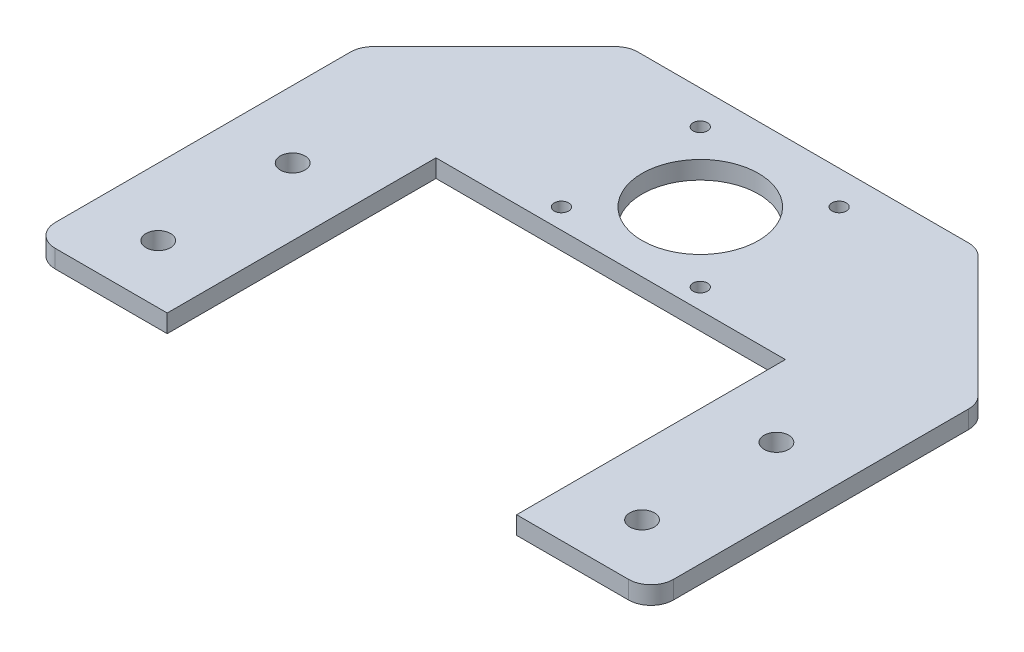
SolidWorks part; units mm, degrees
ref_plane "Front Plane" through (0, 0, 0) normal (0, 0, 1) x (1, 0, 0)
ref_plane "Top Plane" through (0, 0, 0) normal (0, 1, 0) x (1, 0, 0)
ref_plane "Right Plane" through (0, 0, 0) normal (1, 0, 0) x (0, 0, -1)
sketch "Sketch1" plane through (0, 0, 0) normal (0, 1, 0) x (1, 0, 0)
  line L0 (-69, -60) -> (-69, 43)
  line L1 (-69, 43) -> (69, 43)
  line L2 (69, 43) -> (69, -60)
  line L3 (69, -60) -> (39, -60)
  line L4 (39, -60) -> (39, 0)
  line L5 (-4.4, 0) -> (4.4, 0) construction
  line L6 (39, 0) -> (-39, 0)
  line L7 (-39, 0) -> (-39, -60)
  line L8 (-39, -60) -> (-69, -60)
  line L10 (0, 0) -> (0, 59.4938) construction
  line L11 (0, -4.4) -> (0, 4.4) construction
  circle A0 centre (0, 20) radius 13
  dimension "D7" = 26
  dimension "D1" = 78
  dimension "D2" = 60
  dimension "D3" = 60
  dimension "D4" = 43
  dimension "D5" = 30
  dimension "D6" = 30
  dimension "D8" = 20
extrude "Boss-Extrude1" add sketch "Sketch1" along normal blind 4
chamfer "Chamfer1" distance 30 angle 45 2 edges at (-69, 2, -43) (69, 2, -43)
hole_wizard "M3 Clearance Hole1" positions "Sketch3" profile "Sketch2" hole size "M3" standard "ISO"
sketch "Sketch3" plane through (0, 4, 0) normal (0, 1, 0) x (1, 0, 0)
  line L0 (0, -55) -> (0, 55) construction
  line L1 (-55, 0) -> (55, 0) construction
  line L2 (0, 47.128) -> (0, -19.6073) construction
  point P0 (-15.5, 35.5)
  point P2 (-15.5, 4.5)
  point P14 (15.5, 4.5)
  point P15 (15.5, 35.5)
  dimension "D1" = 15.5
  dimension "D2" = 15.5
  dimension "D3" = 4.5
  dimension "D4" = 31
sketch "Sketch2" plane through (-15.5, 4, -35.5) normal (1, 0, 0) x (0, 0, 1)
  line L0 (0, 0) -> (0, 8.9614)
  line L1 (0, 8.9614) -> (1.6, 8)
  line L2 (1.6, 8) -> (1.6, 0)
  line L5 (1.6, 0) -> (0, 0)
  line L10 (0, 8.9614) -> (-1.6, 8) construction
  line L11 (0, -6.35) -> (0, 107.95) construction
  dimension "Hole Dia." = 3.2
  dimension "Hole Depth" = 8
  dimension "Drill Angle" = 118
fillet "Fillet1" radius 5 6 edges at (-69, 2, 60) (-69, 2, -13) (-39, 2, -43) (39, 2, -43) (69, 2, 60) (69, 2, -13)
hole_wizard "M5 Clearance Hole1" positions "Sketch5" profile "Sketch4" hole size "M5" standard "ISO"
sketch "Sketch5" plane through (0, 4, 0) normal (0, 1, 0) x (1, 0, 0)
  line L0 (-55, 0) -> (55, 0) construction
  line L1 (-39, -60) -> (-39, 0) construction
  line L2 (0, -52.3854) -> (0, -7.4062) construction
  line L3 (0, -55) -> (0, 55) construction
  point P0 (-54, -47)
  point P2 (-54, -17)
  point P16 (54, -17)
  point P17 (54, -47)
  dimension "D1" = 30
  dimension "D2" = 17
  dimension "D3" = 15
  dimension "D4" = 15
sketch "Sketch4" plane through (-54, 4, 47) normal (1, 0, 0) x (0, 0, 1)
  line L0 (0, 0) -> (0, 9.6524)
  line L1 (0, 9.6524) -> (2.75, 8)
  line L2 (2.75, 8) -> (2.75, 0)
  line L5 (2.75, 0) -> (0, 0)
  line L10 (0, 9.6524) -> (-2.75, 8) construction
  line L11 (0, -6.35) -> (0, 107.95) construction
  dimension "Hole Dia." = 5.5
  dimension "Hole Depth" = 8
  dimension "Drill Angle" = 118
